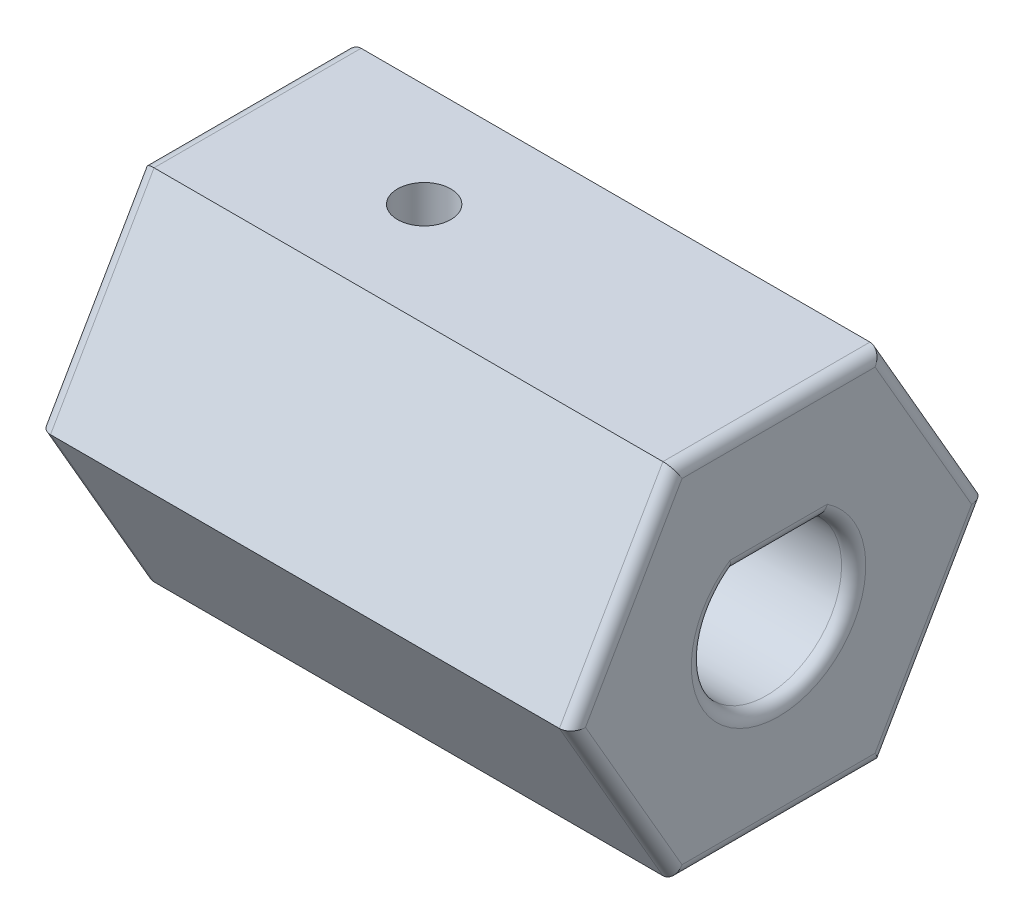
SolidWorks part; units mm, degrees
ref_plane "Alzado" through (0, 0, 0) normal (0, 0, 1) x (1, 0, 0)
ref_plane "Planta" through (0, 0, 0) normal (0, 1, 0) x (1, 0, 0)
ref_plane "Vista lateral" through (0, 0, 0) normal (1, 0, 0) x (0, 0, -1)
sketch "Croquis1" plane through (0, 0, 0) normal (1, 0, 0) x (0, 0, -1)
  line L0 (-1.85, 2.4875) -> (1.85, 2.4875)
  line L1 (-2.1, 3.9875) -> (2.1, 3.9875)
  arc A0 (-1.85, 2.4875) -> (1.85, 2.4875) centre (0, 0) ccw
  arc A1 (-2.1, 3.9875) -> (2.1, 3.9875) centre (0, 0) ccw
  point P4 (0, 2.4875)
  point P11 (0, 3.9875)
  dimension "D2" = 3.1
  dimension "D1" = 3.7
  dimension "D3" = 4.2
  dimension "D4" = 1.5
extrude "Saliente-Extruir1" add sketch "Croquis1" along normal blind 12 contours L0 A0 | L1 A1
sketch "Croquis2" plane through (12, 0, 0) normal (1, 0, 0) x (0, 0, -1)
  line L0 (-1.85, 2.4875) -> (1.85, 2.4875)
  line L1 (-4.2724, -7.4) -> (4.2724, -7.4)
  line L2 (4.2724, -7.4) -> (8.5448, 0)
  line L3 (8.5448, 0) -> (4.2724, 7.4)
  line L4 (4.2724, 7.4) -> (-4.2724, 7.4)
  line L5 (-4.2724, 7.4) -> (-8.5448, 0)
  line L6 (-8.5448, 0) -> (-4.2724, -7.4)
  line L7 (-2.1, 3.9875) -> (2.1, 3.9875) construction
  circle A0 centre (0, 0) radius 7.4 construction
  arc A2 (-2.1, 3.9875) -> (2.1, 3.9875) centre (0, 0) ccw construction
  arc A3 (-1.85, 2.4875) -> (1.85, 2.4875) centre (0, 0) ccw
  arc A4 (-1.85, 2.4875) -> (1.85, 2.4875) centre (0, 0) ccw construction
  dimension "D1" = 14.8
extrude "Saliente-Extruir2" add sketch "Croquis2" against normal blind 12 and the other way blind 10
sketch "Croquis3" plane through (0, 2.4875, 0) normal (0, -1, 0) x (1, 0, 0)
  circle A0 centre (7.375, 0) radius 1.1
  dimension "D2" = 2.2
  dimension "D1" = 7.375
extrude "Cortar-Extruir1" cut sketch "Croquis3" against normal up to surface (4.9125 mm away) up to face at (11, 7.4, 0)
fillet "Redondeo1" radius 0.5 16 edges at (22, 3.7, 6.4086) (22, 7.4, 0) (22, 3.7, -6.4086) (22, -3.7, -6.4086) (22, -7.4, 0) (22, -3.7, 6.4086) (0, -7.4, 0) (0, -3.7, -6.4086) (0, 3.7, -6.4086) (0, 7.4, 0) (0, 3.7, 6.4086) (0, -3.7, 6.4086) (0, -3.1, 0) (22, -3.1, 0) (0, 2.4875, 0) (22, 2.4875, 0)
